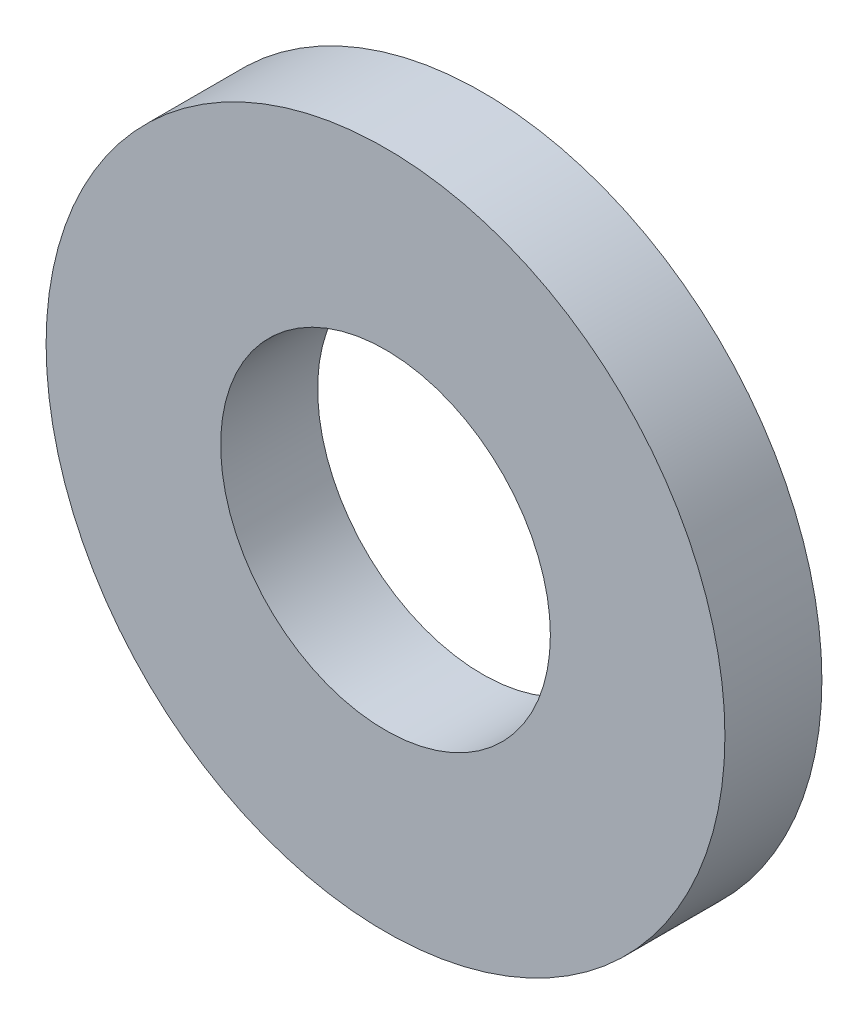
SolidWorks part; units mm, degrees
ref_plane "前视基准面" through (0, 0, 0) normal (0, 0, 1) x (1, 0, 0)
ref_plane "上视基准面" through (0, 0, 0) normal (0, 1, 0) x (1, 0, 0)
ref_plane "右视基准面" through (0, 0, 0) normal (1, 0, 0) x (0, 0, -1)
other "Configuration Table"
sketch "草图1" plane through (0, 0, 0) normal (0, 0, 1) x (1, 0, 0)
  circle A0 centre (0, 0) radius 3.5
  circle A1 centre (0, 0) radius 1.7
extrude "凸台-拉伸1" add sketch "草图1" along normal mid plane 1
